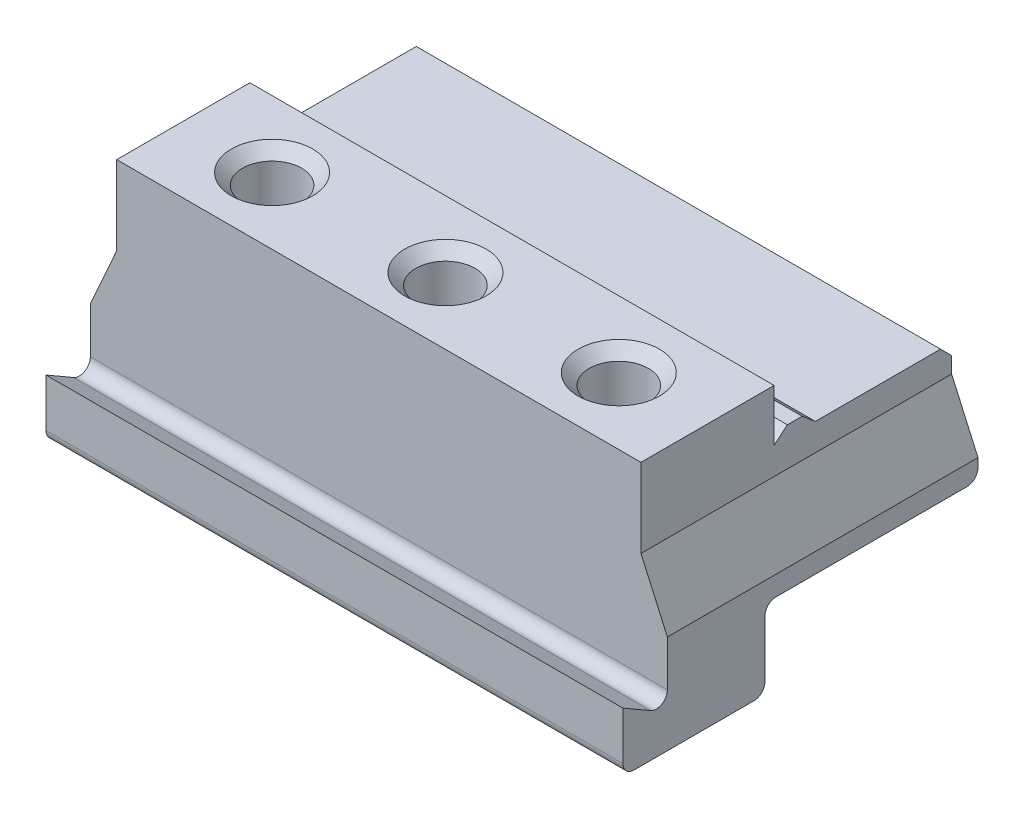
SolidWorks part; units mm, degrees
ref_plane "Front Plane" through (0, 0, 0) normal (0, 0, 1) x (1, 0, 0)
ref_plane "Top Plane" through (0, 0, 0) normal (0, 1, 0) x (1, 0, 0)
ref_plane "Right Plane" through (0, 0, 0) normal (1, 0, 0) x (0, 0, -1)
sketch "Sketch1" plane through (0, 0, 0) normal (1, 0, 0) x (0, 0, -1)
  line L0 (1.5, 0) -> (17.7, 0)
  line L1 (19.2, 1.5) -> (19.2, 9.17)
  line L2 (20.7, 10.67) -> (46.5, 10.67)
  line L3 (48, 12.17) -> (48, 23.5)
  line L4 (46.5, 25) -> (29.5753, 25)
  line L5 (29.5753, 25) -> (27.7876, 26.5)
  line L6 (27.7876, 26.5) -> (25.7876, 26.5)
  line L7 (25.7876, 26.5) -> (24, 25)
  line L8 (24, 25) -> (24, 32)
  line L9 (24, 32) -> (6, 32)
  line L10 (6, 32) -> (6, 7.134)
  line L12 (3.75, 5.8349) -> (0, 8)
  line L13 (0, 8) -> (0, 1.5)
  line L14 (48, 23.5) -> (46.5, 25)
  arc A1 (6, 7.134) -> (3.75, 5.8349) centre (4.5, 7.134) cw
  arc A2 (1.5, 0) -> (0, 1.5) centre (1.5, 1.5) cw
  arc A3 (17.7, 0) -> (19.2, 1.5) centre (17.7, 1.5) ccw
  arc A4 (19.2, 9.17) -> (20.7, 10.67) centre (20.7, 9.17) cw
  arc A5 (46.5, 10.67) -> (48, 12.17) centre (46.5, 12.17) ccw
  point P6 (48, 25)
  point P27 (0, 0)
  dimension "D14" = 1.5
  dimension "D1" = 48
  dimension "D2" = 60
  dimension "D3" = 6
  dimension "D4" = 28.8
  dimension "D5" = 10.67
  dimension "D6" = 7
  dimension "D7" = 18
  dimension "D8" = 100
  dimension "D9" = 40
  dimension "D10" = 2
  dimension "D11" = 32
  dimension "D12" = 0
  dimension "D13" = 1.5
  dimension "D15" = 8
  dimension "D16" = 1.5
  dimension "D17" = 45
extrude "Boss-Extrude1" add sketch "Sketch1" along normal mid plane 78 from offset 39
sketch "Sketch2" plane through (0, 0, -6) normal (0, 0, 1) x (1, 0, 0)
  line L0 (78, 13.33) -> (74.4382, 21.33)
  line L1 (78, 32) -> (78, 7.134) construction
  line L2 (74.4382, 21.33) -> (74.4382, 32)
  line L3 (78, 32) -> (0, 32) construction
  line L4 (39, 36.2986) -> (39, 21.4409) construction
  line L5 (3.5618, 21.33) -> (3.5618, 32)
  line L6 (0, 13.33) -> (3.5618, 21.33)
  line L7 (0, 32) -> (0, 13.33)
  line L8 (3.5618, 32) -> (0, 32)
  line L9 (74.4382, 32) -> (78, 32)
  line L10 (78, 32) -> (78, 13.33)
  dimension "D1" = 24
  dimension "D2" = 10.67
  dimension "D3" = 8
extrude "Cut-Extrude1" cut sketch "Sketch2" against normal blind 42.5
sketch "Sketch3" plane through (0, 32, 0) normal (0, 1, 0) x (1, 0, 0)
  line L0 (39, 24.4185) -> (39, -5.4016) construction
  line L1 (74.4382, 24) -> (74.4382, 6) construction
  line L2 (74.4382, 15) -> (3.5618, 15) construction
  line L3 (3.5618, 24) -> (3.5618, 6) construction
  circle A0 centre (62.4382, 15) radius 4
  circle A1 centre (39, 15) radius 4
  circle A2 centre (15.5618, 15) radius 4
  point P12 (62.4382, 15)
  point P13 (0, 0)
  point P14 (39, 15)
  point P15 (39, 24.4185)
  dimension "D1" = 8
  dimension "D2" = 8
  dimension "D3" = 12
extrude "Cut-Extrude2" cut sketch "Sketch3" against normal blind 10
chamfer "Chamfer1" distance 1.5 angle 45 3 edges at (62.4382, 32, -11) (15.5618, 32, -19) (39, 32, -11)
